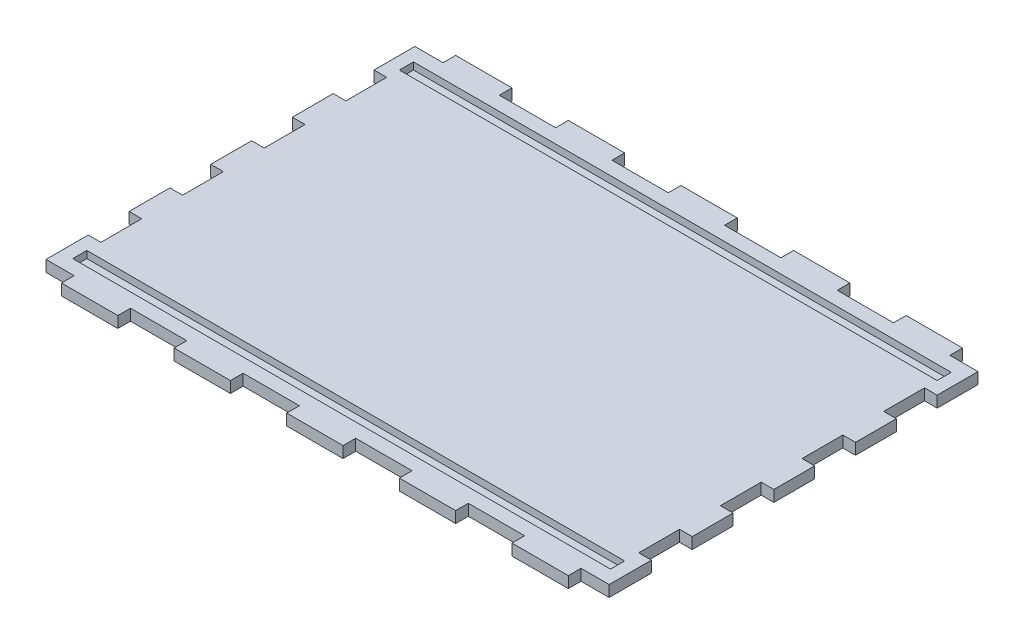
SolidWorks part; units mm, degrees
ref_plane "Front Plane" through (0, 0, 0) normal (0, 0, 1) x (1, 0, 0)
ref_plane "Top Plane" through (0, 0, 0) normal (0, 1, 0) x (1, 0, 0)
ref_plane "Right Plane" through (0, 0, 0) normal (1, 0, 0) x (0, 0, -1)
sketch "Sketch1" plane through (0, 0, 0) normal (0, 1, 0) x (1, 0, 0)
  line L0 (-70, 70) -> (-70, 65.5)
  line L1 (-90, -70) -> (-70, -70)
  line L3 (-90, 70) -> (-70, 70)
  line L5 (-70, 65.5) -> (-50, 65.5)
  line L6 (-30, 65.5) -> (-10, 65.5)
  line L7 (-50, 70) -> (-50, 65.5)
  line L8 (-30, 70) -> (-30, 65.5)
  line L9 (-10, 70) -> (-10, 65.5)
  line L10 (10, 70) -> (10, 65.5)
  line L11 (30, 70) -> (30, 65.5)
  line L12 (50, 70) -> (50, 65.5)
  line L13 (70, 70) -> (70, 65.5)
  line L14 (90, 70) -> (90, 65.5)
  line L15 (-50, 70) -> (-30, 70)
  line L16 (-10, 70) -> (10, 70)
  line L17 (110, 70) -> (110, 65.5) [skipped]
  line L18 (30, 70) -> (50, 70)
  line L19 (70, 70) -> (90, 70)
  line L20 (10, 65.5) -> (30, 65.5)
  line L21 (50, 65.5) -> (70, 65.5)
  line L22 (90, 65.5) -> (100, 65.5)
  line L23 (-90, 70) -> (-90, 65.5)
  line L24 (-90, 65.5) -> (-100, 65.5)
  line L25 (-108.3831, 0) -> (113.6848, 0) construction
  line L26 (-90, -65.5) -> (-100, -65.5)
  line L27 (-90, -70) -> (-90, -65.5)
  line L28 (90, -65.5) -> (100, -65.5)
  line L29 (50, -65.5) -> (70, -65.5)
  line L30 (10, -65.5) -> (30, -65.5)
  line L31 (70, -70) -> (90, -70)
  line L32 (30, -70) -> (50, -70)
  line L33 (-10, -70) -> (10, -70)
  line L34 (-50, -70) -> (-30, -70)
  line L35 (90, -70) -> (90, -65.5)
  line L36 (70, -70) -> (70, -65.5)
  line L37 (50, -70) -> (50, -65.5)
  line L38 (30, -70) -> (30, -65.5)
  line L39 (10, -70) -> (10, -65.5)
  line L40 (-10, -70) -> (-10, -65.5)
  line L41 (-30, -70) -> (-30, -65.5)
  line L42 (-50, -70) -> (-50, -65.5)
  line L43 (-30, -65.5) -> (-10, -65.5)
  line L44 (-70, -65.5) -> (-50, -65.5)
  line L45 (-90, -70) -> (-70, -70)
  line L46 (-70, -70) -> (-70, -65.5)
  line L47 (-50, -70) -> (-30, -70)
  line L48 (-100, 51) -> (-95.5, 51)
  line L49 (-95.5, 51) -> (-95.5, 36.5)
  line L50 (-95.5, 36.5) -> (-100, 36.5)
  line L51 (-100, 51) -> (-100, 65.5)
  line L52 (-100, 36.5) -> (-100, 22)
  line L53 (-100, 22) -> (-95.5, 22)
  line L54 (-95.5, 22) -> (-95.5, 7.5)
  line L55 (-95.5, 7.5) -> (-100, 7.5)
  line L56 (-100, 7.5) -> (-100, -7)
  line L57 (-100, -7) -> (-95.5, -7)
  line L58 (-95.5, -7) -> (-95.5, -21.5)
  line L59 (-95.5, -21.5) -> (-100, -21.5)
  line L60 (-100, -21.5) -> (-100, -36)
  line L61 (-100, -36) -> (-95.5, -36)
  line L62 (-95.5, -36) -> (-95.5, -50.5)
  line L63 (-95.5, -50.5) -> (-100, -50.5)
  line L64 (-100, -50.5) -> (-100, -65.5)
  line L65 (0, 111.7111) -> (0, -88.3658) construction
  line L66 (100, 51) -> (95.5, 51)
  line L67 (100, 36.5) -> (95.5, 36.5)
  line L68 (100, 22) -> (95.5, 22)
  line L69 (100, 7.5) -> (95.5, 7.5)
  line L70 (100, -7) -> (95.5, -7)
  line L71 (100, -21.5) -> (95.5, -21.5)
  line L72 (100, -36) -> (95.5, -36)
  line L73 (100, -50.5) -> (95.5, -50.5)
  line L74 (100, 65.5) -> (100, 51)
  line L75 (95.5, 51) -> (95.5, 36.5)
  line L76 (100, 36.5) -> (100, 22)
  line L77 (95.5, 22) -> (95.5, 7.5)
  line L78 (95.5, -7) -> (95.5, -21.5)
  line L79 (95.5, -36) -> (95.5, -50.5)
  line L80 (100, -65.5) -> (100, -50.5)
  line L81 (100, -36) -> (100, -21.5)
  line L82 (100, 7.5) -> (100, -7)
  point P1 (0, 0)
  point P66 (-100, -58)
  dimension "D4" = 4.5
  dimension "D1" = 4.5
  dimension "D6" = 10
  dimension "D2" = 10
  dimension "D7" = 131
  dimension "D9" = 4.5
  dimension "D10" = 14.5
  dimension "D3" = 4.5
  dimension "D8" = 14.5
  dimension "D11" = 14.5
  dimension "D12" = 4.5
  dimension "D13" = 14.5
  dimension "D14" = 14.5
  dimension "D15" = 4.5
  dimension "D16" = 14.5
  dimension "D17" = 4.5
  dimension "D18" = 14.5
  dimension "D19" = 4.5
  dimension "D20" = 14.5
  dimension "D21" = 4.5
  dimension "D23" = 100
  dimension "D24" = 20
  dimension "D25" = 14.5
  dimension "D5" = 10
  dimension "D22" = 8
extrude "Boss-Extrude1" add sketch "Sketch1" along normal blind 4
sketch "Sketch2" plane through (0, 4, 0) normal (0, 1, 0) x (1, 0, 0)
  line L0 (100, 51) -> (95.5, 51) construction
  line L1 (95.5, 55.5) -> (-95.5, 55.5)
  line L2 (95.5, 55.5) -> (95.5, 60.5)
  line L3 (95.5, 60.5) -> (-95.5, 60.5)
  line L4 (-95.5, 55.5) -> (-95.5, 60.5)
  line L5 (-107.5485, 0) -> (110.4431, 0) construction
  line L6 (-95.5, -55.5) -> (-95.5, -60.5)
  line L7 (95.5, -60.5) -> (-95.5, -60.5)
  line L8 (95.5, -55.5) -> (95.5, -60.5)
  line L9 (95.5, -55.5) -> (-95.5, -55.5)
  dimension "D1" = 4.5
  dimension "D2" = 5
extrude "Cut-Extrude1" cut sketch "Sketch2" against normal blind 2.5
equation "\"D1@Sketch1\"=\"D4@Sketch1\""
equation "\"D2@Sketch1\"=\"D6@Sketch1\""
equation "\"D3@Sketch1\"=\"D9@Sketch1\""
equation "\"D8@Sketch1\"=\"D10@Sketch1\""
equation "\"D11@Sketch1\"=\"D10@Sketch1\""
equation "\"D12@Sketch1\"=\"D9@Sketch1\""
equation "\"D13@Sketch1\"=\"D10@Sketch1\""
equation "\"D14@Sketch1\"=\"D11@Sketch1\""
equation "\"D15@Sketch1\"=\"D12@Sketch1\""
equation "\"D16@Sketch1\"=\"D14@Sketch1\""
equation "\"D17@Sketch1\"=\"D15@Sketch1\""
equation "\"D18@Sketch1\"=\"D16@Sketch1\""
equation "\"D19@Sketch1\"=\"D17@Sketch1\""
equation "\"D20@Sketch1\"=\"D16@Sketch1\""
equation "\"D21@Sketch1\"=\"D19@Sketch1\""
